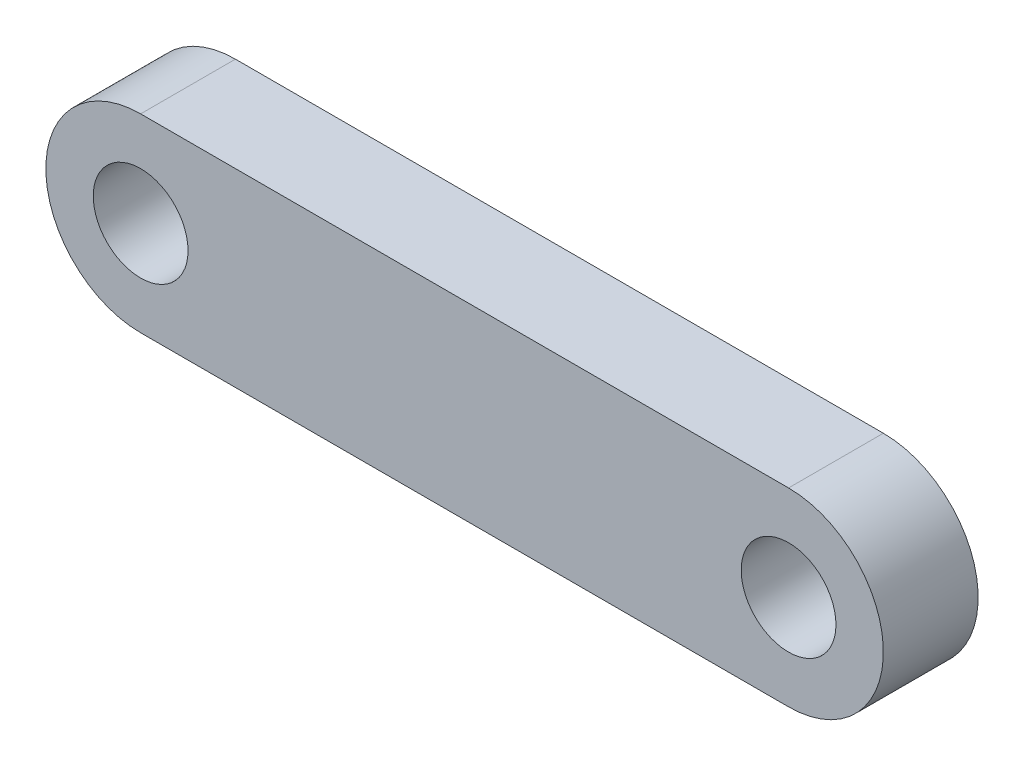
SolidWorks part; units mm, degrees
material "普通碳钢"
ref_plane "前视基准面" through (0, 0, 0) normal (0, 0, 1) x (1, 0, 0)
ref_plane "上视基准面" through (0, 0, 0) normal (0, 1, 0) x (1, 0, 0)
ref_plane "右视基准面" through (0, 0, 0) normal (1, 0, 0) x (0, 0, -1)
sketch "草图1" plane through (0, 0, 0) normal (0, 0, 1) x (1, 0, 0)
  line L0 (0, 0) -> (68.35, 0) construction
  line L1 (0, -10) -> (68.35, -10)
  line L2 (0, 10) -> (68.35, 10)
  arc A0 (0, 10) -> (0, -10) centre (0, 0) ccw
  arc A1 (68.35, 10) -> (68.35, -10) centre (68.35, 0) cw
  dimension "D3" = 68.35
  dimension "D1" = 10
  dimension "D2" = 10
extrude "凸台-拉伸1" add sketch "草图1" along normal blind 10
sketch "草图2" plane through (0, 0, 10) normal (0, 0, 1) x (1, 0, 0)
  circle A0 centre (0, 0) radius 5
  dimension "D1" = 10
extrude "切除-拉伸1" cut sketch "草图2" against normal blind 10
sketch "草图3" plane through (0, 0, 10) normal (0, 0, 1) x (1, 0, 0)
  circle A0 centre (68.35, 0) radius 5
  dimension "D1" = 10
extrude "切除-拉伸2" cut sketch "草图3" against normal blind 10
